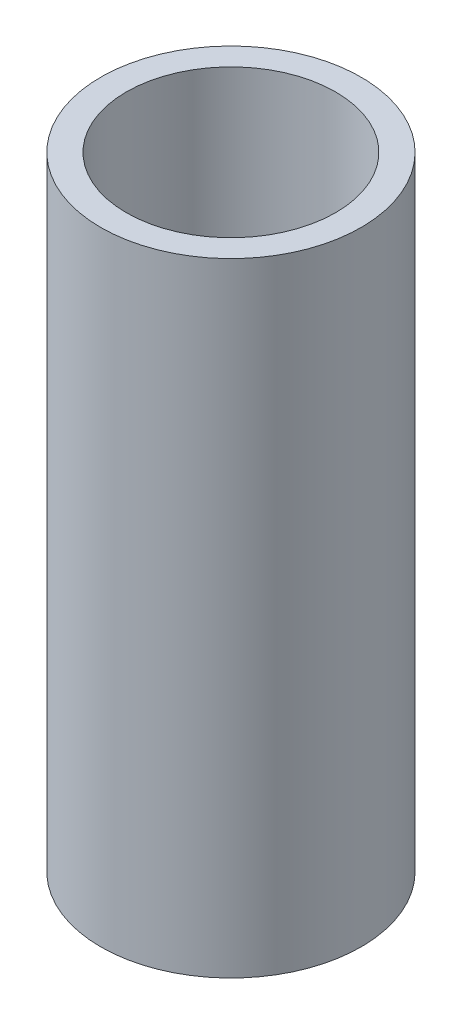
SolidWorks part; units mm, degrees
ref_plane "Front Plane" through (0, 0, 0) normal (0, 0, 1) x (1, 0, 0)
ref_plane "Top Plane" through (0, 0, 0) normal (0, 1, 0) x (1, 0, 0)
ref_plane "Right Plane" through (0, 0, 0) normal (1, 0, 0) x (0, 0, -1)
sketch "Sketch1" plane through (0, 0, 0) normal (0, 1, 0) x (1, 0, 0)
  circle A0 centre (0, 0) radius 3.275
  circle A1 centre (0, 0) radius 4.075
  dimension "D1" = 6.55
  dimension "D2" = 8.15
extrude "Boss-Extrude1" add sketch "Sketch1" along normal blind 19.5
